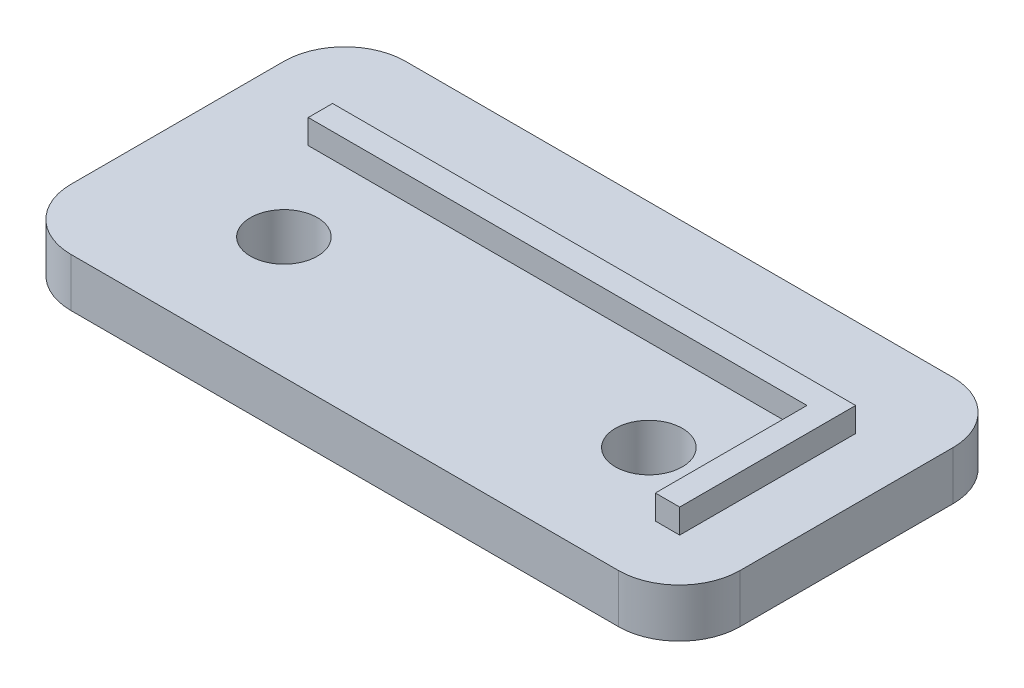
SolidWorks part; units mm, degrees
ref_plane "前视基准面" through (0, 0, 0) normal (0, 0, 1) x (1, 0, 0)
ref_plane "上视基准面" through (0, 0, 0) normal (0, 1, 0) x (1, 0, 0)
ref_plane "右视基准面" through (0, 0, 0) normal (1, 0, 0) x (0, 0, -1)
other "Configuration Table"
sketch "草图1" plane through (0, 0, 0) normal (0, 1, 0) x (1, 0, 0)
  line L1 (0, 0) -> (-55, 0)
  line L2 (0, 0) -> (0, 27.5)
  line L3 (0, 27.5) -> (-55, 27.5)
  line L4 (-55, 0) -> (-55, 27.5)
  dimension "D1" = 55
  dimension "D2" = 27.5
extrude "凸台-拉伸1" add sketch "草图1" along normal blind 4
sketch "草图2" plane through (0, 4, 0) normal (0, 1, 0) x (1, 0, 0)
  line L0 (-27.5, 0) -> (-27.5, 4.9209)
  line L1 (-55, 0) -> (0, 0) construction
  circle A0 centre (-42.5, 10) radius 2.75
  circle A1 centre (-12.5, 10) radius 2.75
  dimension "D1" = 5.5
  dimension "D2" = 30
  dimension "D3" = 10
extrude "切除-拉伸1" cut sketch "草图2" against normal through all contours A0 | A1
fillet "圆角1" radius 5 4 edges at (-55, 2, -27.5) (0, 2, -27.5) (0, 2, 0) (-55, 2, 0)
sketch "草图4" plane through (0, 4, 0) normal (0, 1, 0) x (1, 0, 0)
  line L0 (-27.5, 27.5) -> (-27.5, 11.5) construction
  line L1 (-48, 19.5) -> (-7, 19.5)
  line L2 (-48, 19.5) -> (-48, 17.5)
  line L3 (-48, 17.5) -> (-7, 17.5)
  line L4 (-7, 19.5) -> (-7, 17.5)
  line L5 (-7, 17.5) -> (-5, 17.5)
  line L6 (-7, 17.5) -> (-7, 5.0358)
  line L7 (-7, 5.0358) -> (-5, 5.0358)
  line L8 (-5, 17.5) -> (-5, 5.0358)
  line L9 (-5, 27.5) -> (-50, 27.5) construction
  line L11 (-7, 19.5) -> (-5, 19.5)
  line L12 (-7, 19.5) -> (-7, 17.5)
  line L13 (-7, 17.5) -> (-5, 17.5)
  line L14 (-5, 19.5) -> (-5, 17.5)
  point P11 (-27.5, 19.5)
  dimension "D1" = 41
  dimension "D2" = 2
  dimension "D3" = 2
  dimension "D4" = 8
extrude "凸台-拉伸6" add sketch "草图4" along normal blind 2 contours L1 L0 L3 L4 | L14 L11 L4 L5 | L8 L5 L6 L7 | L0 L1 L2 L3
equation "\"5。5\"=7.33194"
